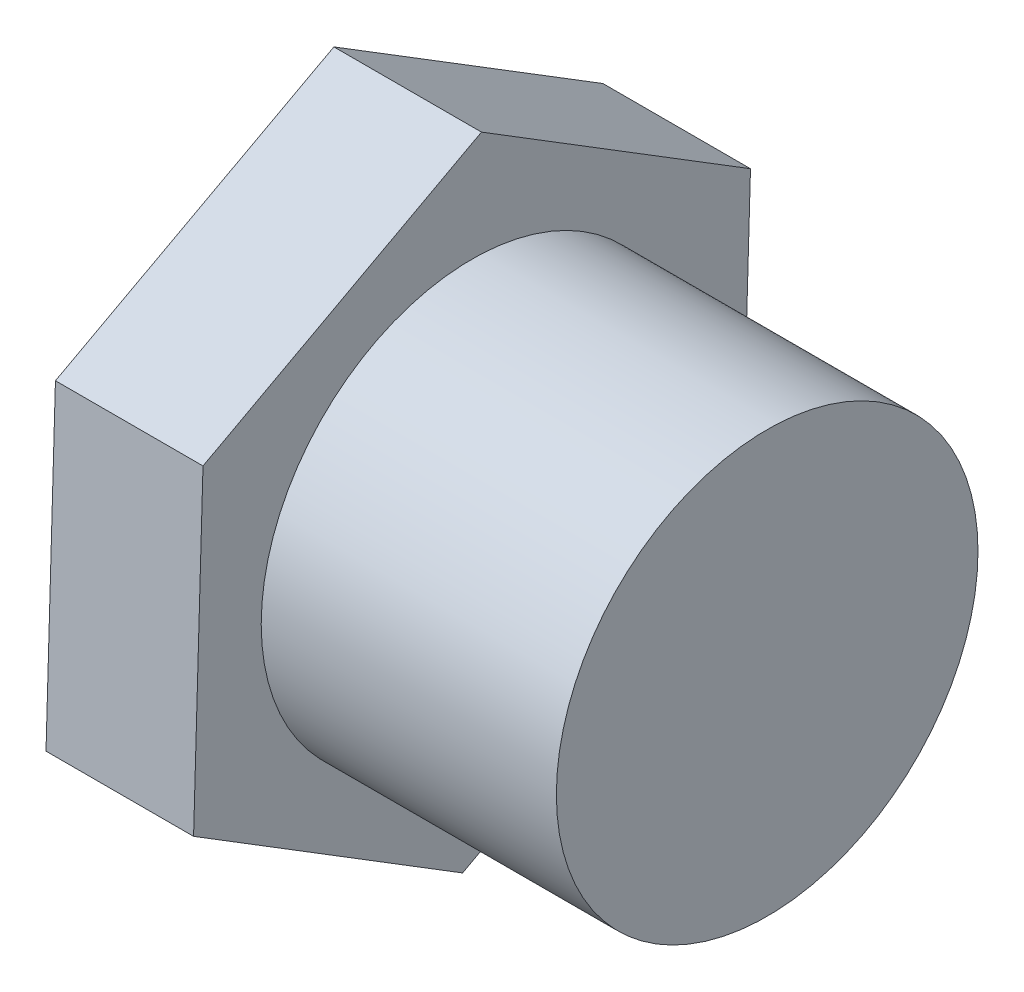
SolidWorks part; units mm, degrees
ref_plane "Alzado" through (0, 0, 0) normal (0, 0, 1) x (1, 0, 0)
ref_plane "Planta" through (0, 0, 0) normal (0, 1, 0) x (1, 0, 0)
ref_plane "Vista lateral" through (0, 0, 0) normal (1, 0, 0) x (0, 0, -1)
sketch "Croquis1" plane through (0, 0, 0) normal (1, 0, 0) x (0, 0, -1)
  circle A0 centre (0, 0) radius 10
  dimension "D1" = 20
extrude "Saliente-Extruir1" add sketch "Croquis1" along normal blind 14
cosmetic thread "Rosca cosmética4" parameters "D2"=17.797
cosmetic thread "Rosca cosmética5" parameters "D2"=17.797
sketch "Croquis2" plane through (0, 0, 0) normal (-1, 0, 0) x (0, 0, 1)
  circle A0 centre (0, 0) radius 15
  dimension "D1" = 30
extrude "Saliente-Extruir2" add sketch "Croquis2" along normal blind 7
sketch "Croquis5" plane through (-7, 0, 0) normal (-1, 0, 0) x (0, 0, 1)
  line L1 (-0.4474, 14.9933) -> (-13.2083, 7.1092)
  line L2 (-13.2083, 7.1092) -> (-12.7609, -7.8841)
  line L3 (-12.7609, -7.8841) -> (0.4474, -14.9933)
  line L4 (0.4474, -14.9933) -> (13.2083, -7.1092)
  line L5 (13.2083, -7.1092) -> (12.7609, 7.8841)
  line L6 (12.7609, 7.8841) -> (-0.4474, 14.9933)
  circle A0 centre (0, 0) radius 12.9904 construction
  circle A1 centre (0, 0) radius 15
  circle M8 centre (0, 0) radius 15
  dimension "D1" = 30
extrude "Cortar-Extruir1" cut sketch "Croquis5" against normal through all contours L1 M8 | L2 M8 | L3 M8 | L4 M8 | L5 M8 | L6 M8
